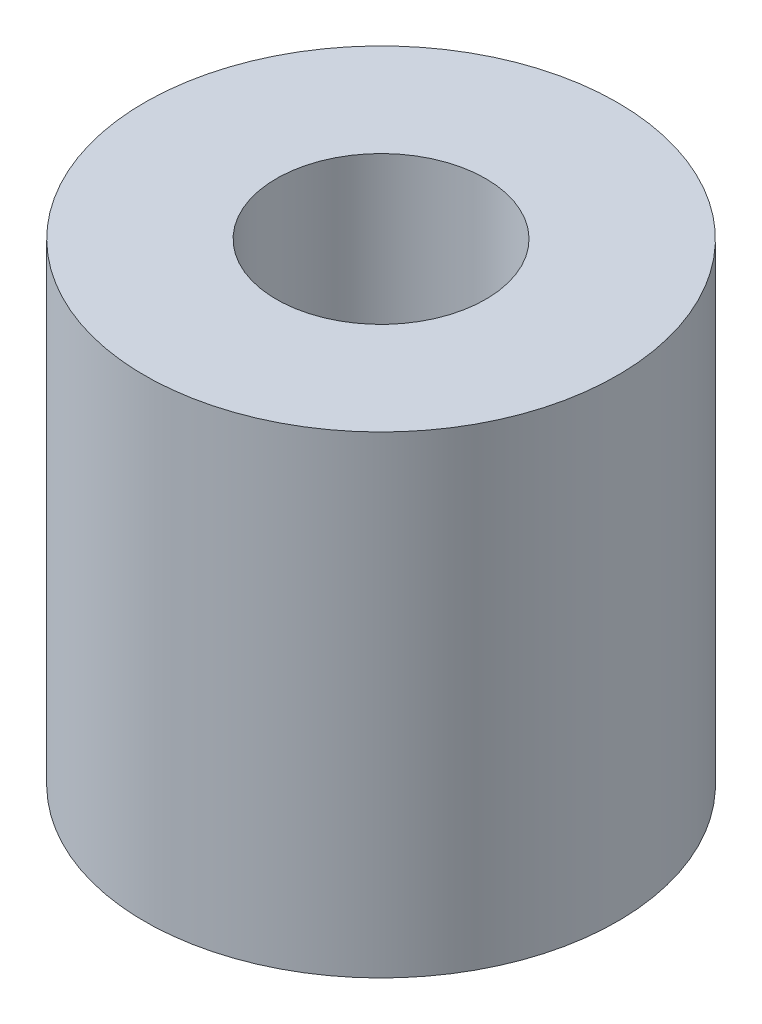
SolidWorks part; units mm, degrees
ref_plane "Front Plane" through (0, 0, 0) normal (0, 0, 1) x (1, 0, 0)
ref_plane "Top Plane" through (0, 0, 0) normal (0, 1, 0) x (1, 0, 0)
ref_plane "Right Plane" through (0, 0, 0) normal (1, 0, 0) x (0, 0, -1)
sketch "Sketch1" plane through (0, 0, 0) normal (0, 1, 0) x (1, 0, 0)
  circle A0 centre (0, 0) radius 2.1082
  circle A1 centre (0, 0) radius 4.7625
  dimension "D1" = 9.525
  dimension "D2" = 4.2164
extrude "Boss-Extrude1" add sketch "Sketch1" along normal blind 9.525
